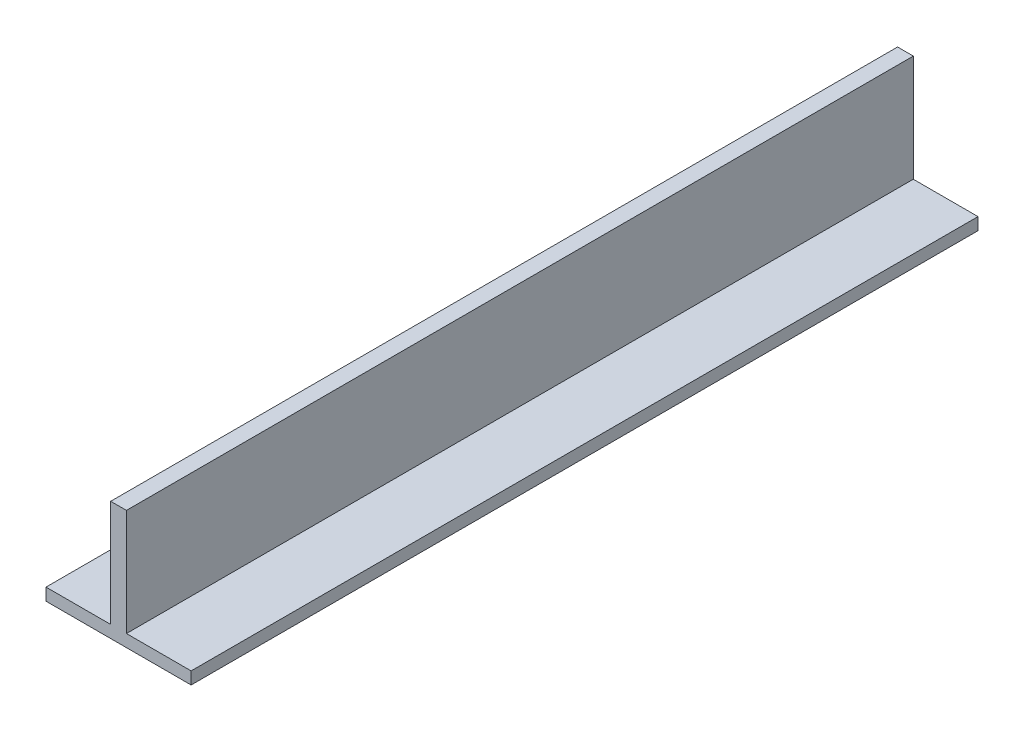
SolidWorks part; units mm, degrees
ref_plane "Plan de face" through (0, 0, 0) normal (0, 0, 1) x (1, 0, 0)
ref_plane "Plan de dessus" through (0, 0, 0) normal (0, 1, 0) x (1, 0, 0)
ref_plane "Plan de droite" through (0, 0, 0) normal (1, 0, 0) x (0, 0, -1)
sketch "Esquisse1" plane through (0, 0, 0) normal (0, 0, 1) x (1, 0, 0)
  line L0 (0, 0) -> (83, 0)
  line L1 (83, 0) -> (83, 7)
  line L2 (83, 7) -> (46, 7)
  line L3 (46, 7) -> (46, 68)
  line L4 (46, 68) -> (37, 68)
  line L5 (37, 68) -> (37, 7)
  line L6 (37, 7) -> (0, 7)
  line L7 (0, 7) -> (0, 0)
  dimension "D1" = 7
  dimension "D2" = 9
  dimension "D3" = 83
  dimension "D4" = 68
extrude "Boss.-Extru.1" add sketch "Esquisse1" along normal blind 450
sketch "Esquisse2" plane through (0, 7, 0) normal (0, 1, 0) x (1, 0, 0)
  line L0 (0, 0) -> (0, -224)
  line L1 (0, -450) -> (0, 0) construction
  line L2 (37, 0) -> (0, 0)
  line L3 (37, -224) -> (37, 0)
  line L7 (0, -224) -> (37, -224)
  dimension "D3" = 224
extrude "Enlèv. mat.-Extru.1" cut sketch "Esquisse2" against normal up to vertex (7 mm away) up to point (83, 0, 0)
